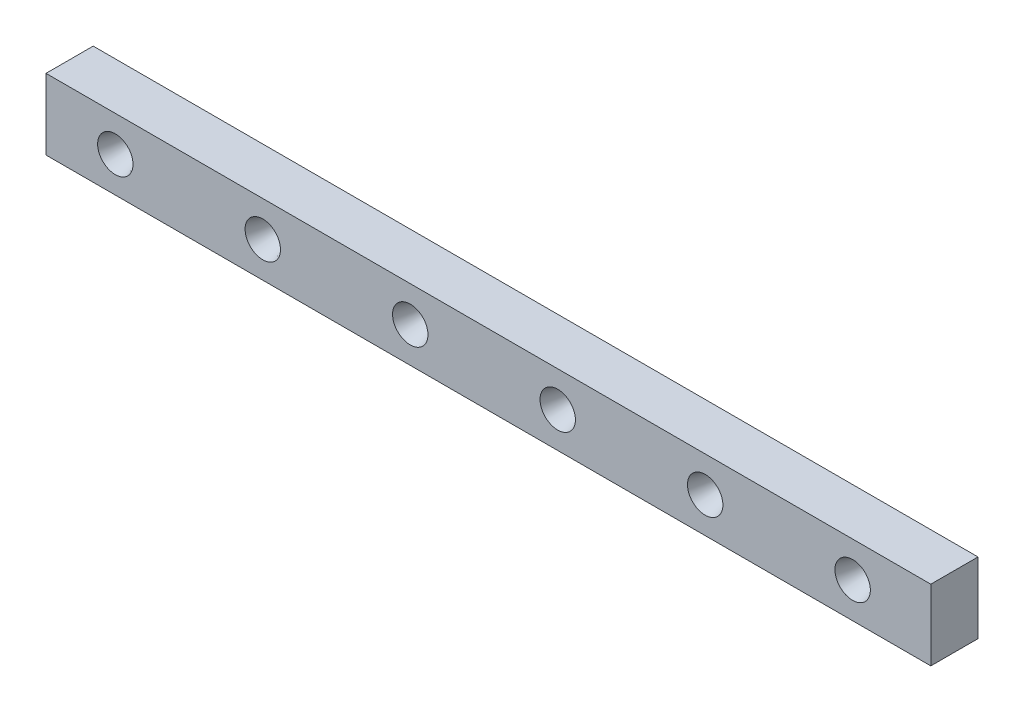
SolidWorks part; units mm, degrees
ref_plane "Top Plane" through (0, 0, 0) normal (0, 0, 1) x (1, 0, 0)
ref_plane "Right Plane" through (0, 0, 0) normal (0, 1, 0) x (1, 0, 0)
ref_plane "Front Plane" through (0, 0, 0) normal (1, 0, 0) x (0, 0, -1)
sketch "Sketch1" plane through (0, 0, 0) normal (1, 0, 0) x (0, 0, -1)
  line L1 (-4, 6) -> (4, 6)
  line L2 (-4, 6) -> (-4, -6)
  line L3 (-4, -6) -> (4, -6)
  line L4 (4, 6) -> (4, -6)
  line L5 (-4, 6) -> (4, -6) construction
  line L6 (-4, -6) -> (4, 6) construction
  point P4 (0, 0)
  point P5 (0, 0)
  dimension "D1" = 12
  dimension "D2" = 8
extrude "Boss-Extrude1" add sketch "Sketch1" along normal blind 150
ref_plane "Plane1" through (11.75, 0, 0) normal (-1, 0, 0) x (0, 0, 1)
sketch "Sketch4" plane through (11.75, 0, 0) normal (-1, 0, 0) x (0, 0, 1)
  line L0 (4, 0) -> (-4, 0)
  line L1 (-4, 0) -> (-4, -1.75)
  line L2 (-4, -1.75) -> (0, -1.75)
  line L3 (0, -1.75) -> (4, -3)
  line L4 (4, -3) -> (4, 0)
  line L5 (-4, -6) -> (-4, 6) construction
  line L6 (0, 0) -> (0, -1.75) construction
  point P3 (0, 0)
  dimension "D1" = 1.75
  dimension "D2" = 3
revolve "Cut-Revolve1" cut sketch "Sketch4" angle 360 about L0
pattern_linear "LPattern1" count 6 spacing 25 along (1, 0, 0) of "Cut-Revolve1"
